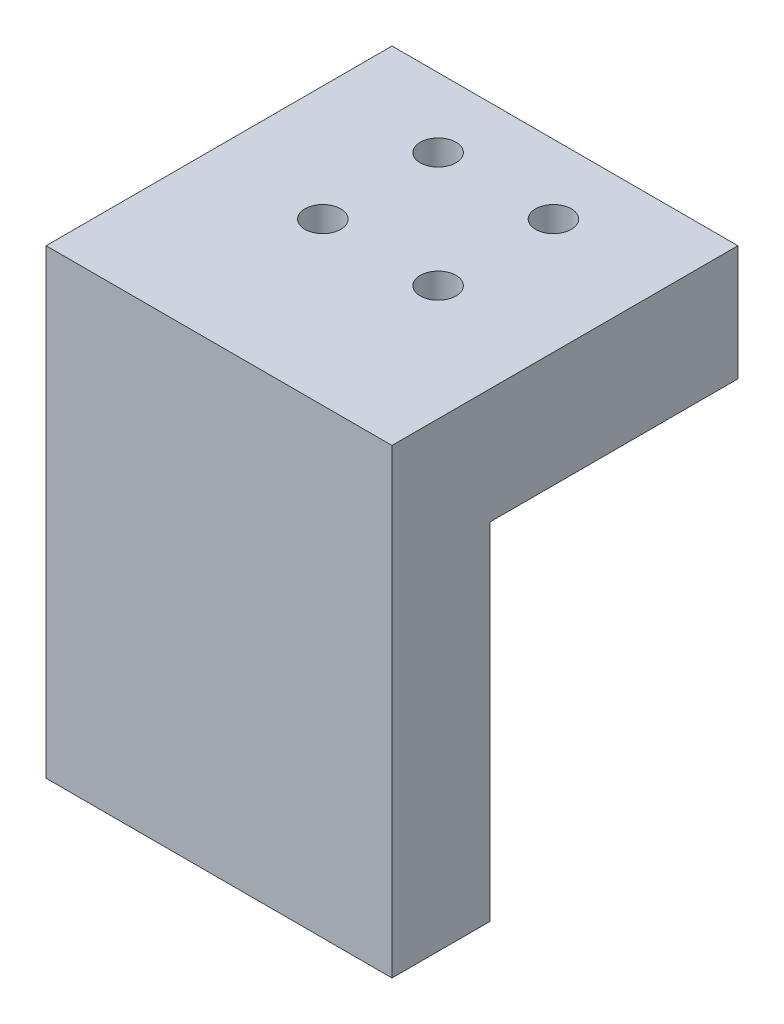
SolidWorks part; units mm, degrees
ref_plane "前视基准面" through (0, 0, 0) normal (0, 0, 1) x (1, 0, 0)
ref_plane "上视基准面" through (0, 0, 0) normal (0, 1, 0) x (1, 0, 0)
ref_plane "右视基准面" through (0, 0, 0) normal (1, 0, 0) x (0, 0, -1)
sketch "草图1" plane through (0, 0, 0) normal (0, 1, 0) x (1, 0, 0)
  line L1 (-15, -15) -> (15, -15)
  line L2 (-15, -15) -> (-15, 15)
  line L3 (-15, 15) -> (15, 15)
  line L4 (15, -15) -> (15, 15)
  line L5 (-15, -15) -> (15, 15) construction
  line L6 (-15, 15) -> (15, -15) construction
  point P0 (0, 0)
  dimension "D1" = 30
  dimension "D2" = 30
extrude "凸台-拉伸1" add sketch "草图1" along normal blind 10
sketch "草图3" plane through (0, 0, 0) normal (0, -1, 0) x (1, 0, 0)
  line L0 (0, 0) -> (0, 11.9997) construction
  line L1 (-15, -15) -> (-15, 15) construction
  line L2 (-15, 6.5) -> (15, 6.5)
  line L3 (-15, 6.5) -> (-15, 13.5)
  line L4 (-15, 13.5) -> (15, 13.5)
  line L5 (15, 6.5) -> (15, 13.5)
  line L6 (-15, 6.5) -> (15, 13.5) construction
  line L7 (-15, 13.5) -> (15, 6.5) construction
  line L9 (-15, 15) -> (15, 15)
  line L10 (-15, 15) -> (-15, 13.5)
  line L11 (-15, 13.5) -> (15, 13.5)
  line L12 (15, 15) -> (15, 13.5)
  point P3 (0, 10)
  line M9 (15, -15) -> (15, 15)
  line M10 (15, 15) -> (-15, 15)
  line M11 (-15, 15) -> (-15, -15)
  dimension "D1" = 7
  dimension "D2" = 10
extrude "凸台-拉伸3" add sketch "草图3" along normal blind 30 contours L4 L2 M11 M9 | L4 M11 M9 M10
sketch "草图4" plane through (0, 0, 0) normal (0, -1, 0) x (1, 0, 0)
  line L0 (0, 0) -> (0, -15.9735) construction
  line L2 (-5, -9) -> (5, -9) construction
  line L3 (-5, -9) -> (-5, 1) construction
  line L4 (-5, 1) -> (5, 1) construction
  line L5 (5, -9) -> (5, 1) construction
  line L6 (-5, -9) -> (5, 1) construction
  line L7 (-5, 1) -> (5, -9) construction
  circle A0 centre (-5, 1) radius 1.55
  circle A1 centre (5, 1) radius 1.55
  circle A2 centre (5, -9) radius 1.55
  circle A3 centre (-5, -9) radius 1.55
  point P3 (0, -4)
  dimension "D4" = 3.1
  dimension "D1" = 10
  dimension "D2" = 10
  dimension "D3" = 4
extrude "切除-拉伸1" cut sketch "草图4" against normal blind 30 contours A1 | A2 | A0 | A3
sketch "草图5" plane through (0, 0, 0) normal (0, -1, 0) x (1, 0, 0)
  circle A0 centre (-5, 1) radius 3.5
  circle A1 centre (5, 1) radius 3.5
  circle A2 centre (-5, -9) radius 3.5
  circle A3 centre (5, -9) radius 3.5
  circle M5 centre (5, -9) radius 1.55
  circle M7 centre (-5, -9) radius 1.55
  circle M8 centre (5, 1) radius 1.55
  dimension "D1" = 7
extrude "切除-拉伸2" cut sketch "草图5" against normal blind 3 contours A1 M8 | A3 M5 | A2 M7 | A0
